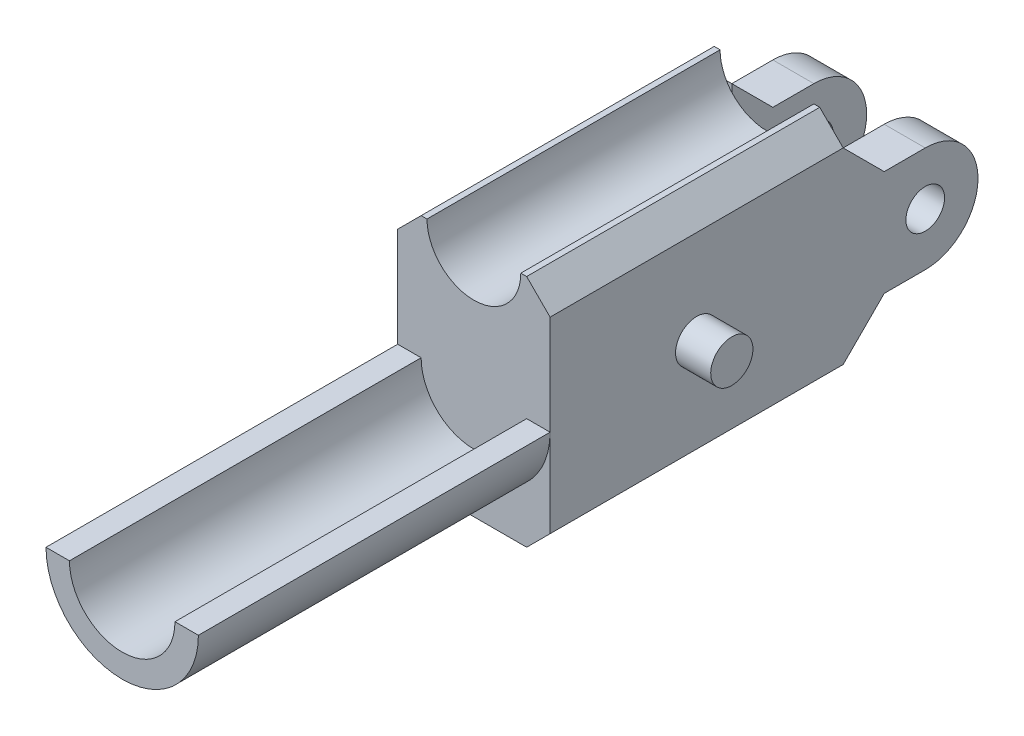
SolidWorks part; units mm, degrees
ref_plane "Front Plane" through (0, 0, 0) normal (0, 0, 1) x (1, 0, 0)
ref_plane "Top Plane" through (0, 0, 0) normal (0, 1, 0) x (1, 0, 0)
ref_plane "Right Plane" through (0, 0, 0) normal (1, 0, 0) x (0, 0, -1)
sketch "Sketch1" plane through (0, 0, 0) normal (0, 0, 1) x (1, 0, 0)
  line L0 (6.5, 0) -> (4.5, 0)
  line L1 (-6.5, 0) -> (-4.5, 0)
  arc A0 (6.5, 0) -> (-6.5, 0) centre (0, 0) cw
  arc A1 (4.5, 0) -> (-4.5, 0) centre (0, 0) cw
  arc A2 (6.5, 0) -> (-6.5, 0) centre (0, 0) cw construction
  point P1 (0, 0)
  point P3 (0, 0)
  point P4 (0, 0)
  point P9 (0, 0)
  dimension "D1" = 13
  dimension "D3" = 2
extrude "Boss-Extrude1" add sketch "Sketch1" along normal blind 30
sketch "Sketch2" plane through (0, 0, 0) normal (0, 0, -1) x (-1, 0, 0)
  line L1 (6.5, 10.5) -> (-6.5, 10.5)
  line L2 (6.5, 10.5) -> (6.5, -9.5)
  line L3 (6.5, -9.5) -> (-6.5, -9.5)
  line L4 (-6.5, 10.5) -> (-6.5, -9.5)
  line L5 (6.5, 10.5) -> (-6.5, -9.5) construction
  line L6 (6.5, -9.5) -> (-6.5, 10.5) construction
  arc A1 (-6.5, 0) -> (6.5, 0) centre (0, 0) ccw construction
  point P0 (0, 0.5)
  point P5 (0, -9.5)
  dimension "D1" = 20
  dimension "2" = 3
extrude "Boss-Extrude2" add sketch "Sketch2" along normal blind 25
chamfer "Chamfer1" distance 2 angle 45 4 edges at (-6.5, -9.5, -12.5) (6.5, -9.5, -12.5) (6.5, 10.5, -12.5) (-6.5, 10.5, -12.5)
sketch "Sketch3" plane through (0, 0, -25) normal (0, 0, -1) x (-1, 0, 0)
  line L0 (4.5, 10.5) -> (-4.5, 10.5) construction
  circle A0 centre (0, 10.5) radius 4
  dimension "D1" = 8
extrude "Cut-Extrude1" cut sketch "Sketch3" against normal blind 40
sketch "Sketch4" plane through (0, 0, 0) normal (1, 0, 0) x (0, 0, -1)
  line L0 (12.5, 8.5) -> (12.5, -7.5) construction
  line L1 (25, 8.5) -> (0, 8.5) construction
  line L2 (0, -7.5) -> (25, -7.5) construction
  circle A0 centre (12.5, 0.5) radius 1.8
  dimension "D1" = 3.6
extrude "Boss-Extrude3" add sketch "Sketch4" along normal mid plane 19
sketch "Sketch5" plane through (6.5, 0, 0) normal (1, 0, 0) x (0, 0, -1)
  line L0 (25, 0.5) -> (36.5, 0.5) construction
  line L1 (25, 8.5) -> (25, -7.5) construction
  line L2 (32, 5) -> (28.5, 5)
  line L3 (28.5, 5) -> (25, 8.5)
  line L4 (32, -4) -> (28.5, -4)
  line L5 (28.5, -4) -> (25, -7.5)
  line L6 (25, 8.5) -> (25, -7.5)
  circle A0 centre (32, 0.5) radius 1.65
  arc A1 (32, -4) -> (32, 5) centre (32, 0.5) ccw
  dimension "D1" = 3.3
  dimension "D2" = 9
  dimension "D3" = 45
  dimension "D4" = 3.5
extrude "Boss-Extrude4" add sketch "Sketch5" against normal up to surface (13 mm away) up to face at (-6.5, 2.3, -12.5)
sketch "Sketch6" plane through (0, 5, 0) normal (0, 1, 0) x (1, 0, 0)
  line L0 (0, 25) -> (0, 36.5) construction
  line L1 (-3.4641, 25) -> (3.4641, 25) construction
  line L2 (6.5, 36.5) -> (-6.5, 36.5) construction
  line L3 (-3.4641, 25) -> (3.4641, 25) construction
  line L4 (3, 36.5) -> (-3, 36.5)
  line L5 (3, 36.5) -> (3, 25)
  line L6 (3, 25) -> (-3, 25)
  line L7 (-3, 36.5) -> (-3, 25)
  line L8 (3, 36.5) -> (-3, 25) construction
  line L9 (3, 25) -> (-3, 36.5) construction
  point P6 (0, 30.75)
  dimension "D1" = 6
extrude "Cut-Extrude2" cut sketch "Sketch6" against normal through all both and the other way through all
